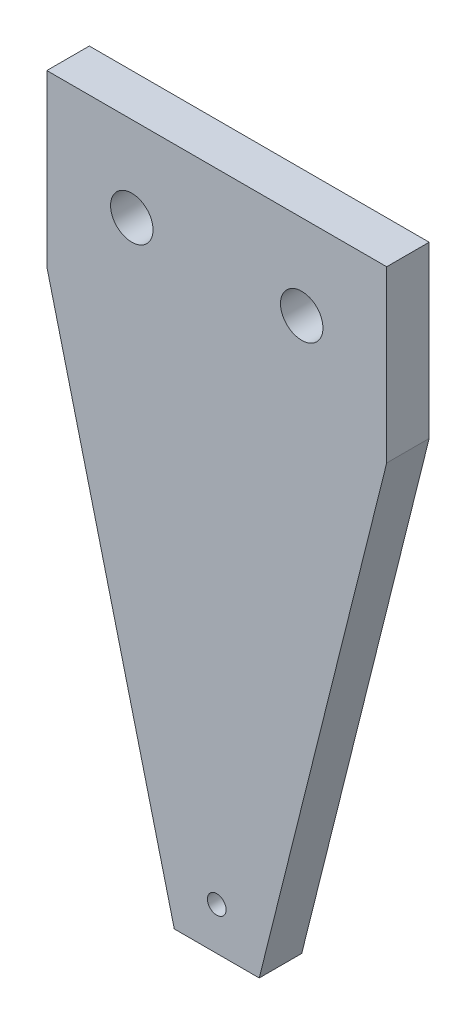
SolidWorks part; units mm, degrees
ref_plane "Alzado" through (0, 0, 0) normal (0, 0, 1) x (1, 0, 0)
ref_plane "Planta" through (0, 0, 0) normal (0, 1, 0) x (1, 0, 0)
ref_plane "Vista lateral" through (0, 0, 0) normal (1, 0, 0) x (0, 0, -1)
sketch "Croquis1" plane through (0, 0, 0) normal (0, 0, 1) x (1, 0, 0)
  line L0 (0, 0) -> (0, 10) construction
  line L1 (-20, 10) -> (20, 10)
  line L2 (-20, 10) -> (-20, -10)
  line L3 (-20, -10) -> (20, -10)
  line L4 (20, 10) -> (20, -10)
  line L5 (-20, 10) -> (20, -10) construction
  line L6 (-20, -10) -> (20, 10) construction
  line L7 (0, 0) -> (-10, 0) construction
  circle A0 centre (-10, 0) radius 2.5
  circle A1 centre (10, 0) radius 2.5
  point P0 (0, 0)
  dimension "D1" = 5
  dimension "D2" = 10
extrude "Saliente-Extruir1" add sketch "Croquis1" along normal blind 5
sketch "Croquis2" plane through (0, 0, 5) normal (0, 0, 1) x (1, 0, 0)
  line L0 (0, 0) -> (0, -65) construction
  line L1 (-20, -10) -> (-5, -70)
  line L2 (-5, -60) -> (5, -60)
  line L3 (-5, -60) -> (-5, -70)
  line L4 (-5, -70) -> (5, -70)
  line L5 (5, -60) -> (5, -70)
  line L6 (-5, -60) -> (5, -70) construction
  line L7 (-5, -70) -> (5, -60) construction
  line L8 (5, -70) -> (20, -10)
  line L9 (-20, -10) -> (20, -10) construction
  circle A0 centre (0, -65) radius 1.1
  line M9 (-20, -10) -> (20, -10)
  dimension "D1" = 2.2
  dimension "D2" = 10
  dimension "D3" = 60
extrude "Saliente-Extruir2" add sketch "Croquis2" against normal blind 5 contours L5 L8 L1 L3 L2 M9 | L5 L2 L3 L4 A0
